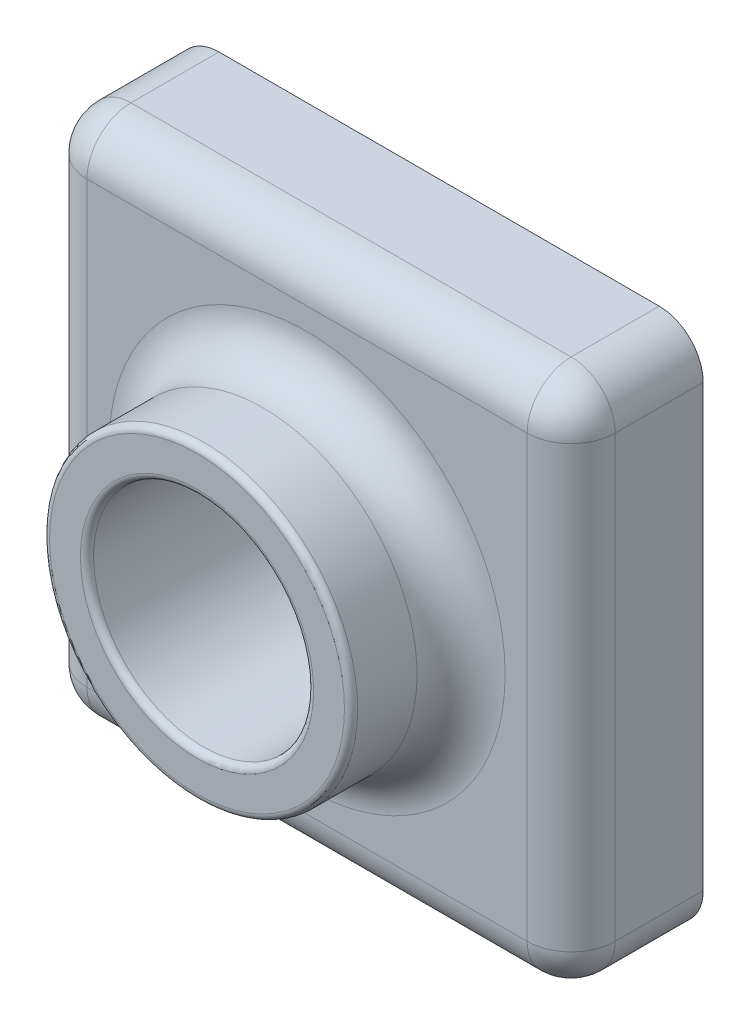
SolidWorks part; units mm, degrees
ref_plane "Front Plane" through (0, 0, 0) normal (0, 0, 1) x (1, 0, 0)
ref_plane "Top Plane" through (0, 0, 0) normal (0, 1, 0) x (1, 0, 0)
ref_plane "Right Plane" through (0, 0, 0) normal (1, 0, 0) x (0, 0, -1)
sketch "Sketch1" plane through (0, 0, 0) normal (0, 0, 1) x (1, 0, 0)
  line L1 (0, 0) -> (-120, 0)
  line L2 (0, 0) -> (0, -120)
  line L3 (0, -120) -> (-120, -120)
  line L4 (-120, 0) -> (-120, -120)
  dimension "D1" = 120
  dimension "D2" = 120
extrude "Boss-Extrude1" add sketch "Sketch1" along normal blind 30
sketch "Sketch2" plane through (0, 0, 30) normal (0, 0, 1) x (1, 0, 0)
  line L0 (0, 0) -> (-120, 0) construction
  line L1 (-120, 0) -> (-120, -120) construction
  circle A0 centre (-60, -60) radius 35
  dimension "D1" = 70
  dimension "D2" = 60
  dimension "D3" = 60
extrude "Boss-Extrude2" add sketch "Sketch2" along normal blind 25
sketch "Sketch3" plane through (0, 0, 55) normal (0, 0, 1) x (1, 0, 0)
  circle A0 centre (-60, -60) radius 25
  dimension "D1" = 50
extrude "Cut-Extrude1" cut sketch "Sketch3" against normal through all
fillet "Fillet1" radius 10 9 edges at (-25, -60, 30) (-120, -120, 15) (-120, -60, 30) (0, -120, 15) (-60, -120, 30) (0, -60, 30) (0, 0, 15) (-120, 0, 15) (-60, 0, 30)
fillet "Fillet2" radius 1.5 2 edges at (-35, -60, 55) (-25, -60, 55)
shell "Shell1" thickness 2
